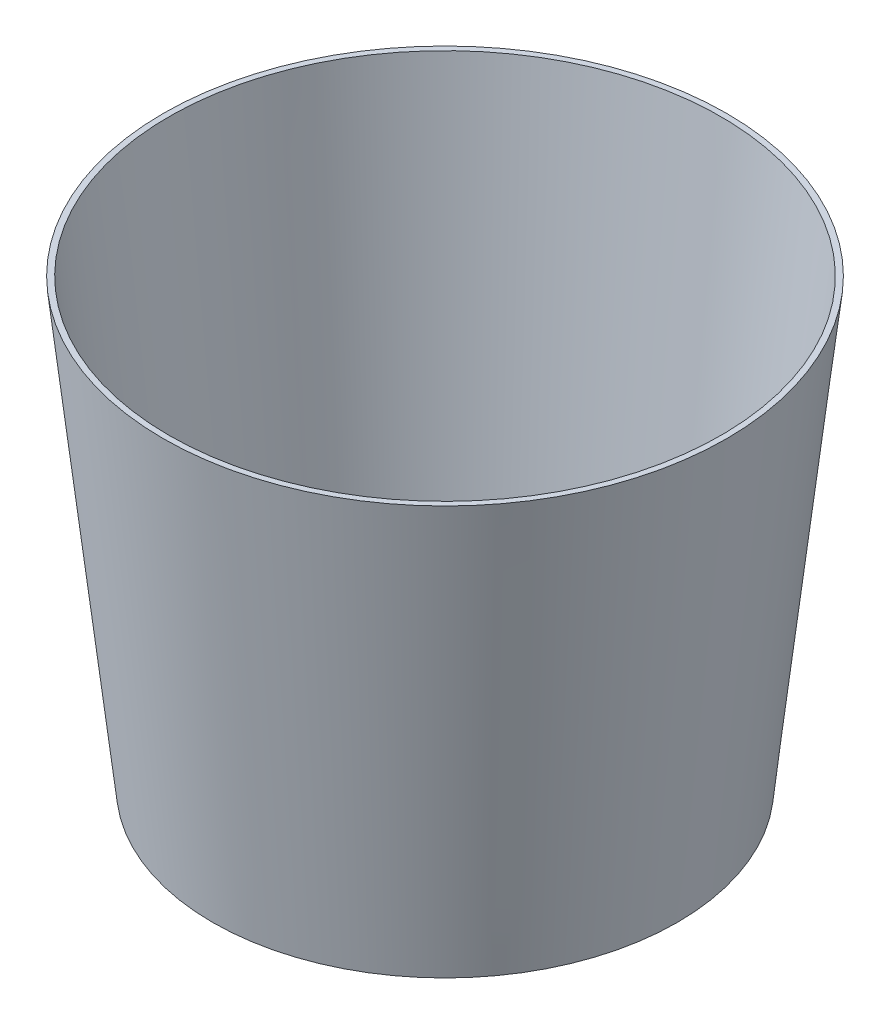
SolidWorks part; units mm, degrees
ref_plane "前视基准面" through (0, 0, 0) normal (0, 0, 1) x (1, 0, 0)
ref_plane "上视基准面" through (0, 0, 0) normal (0, 1, 0) x (1, 0, 0)
ref_plane "右视基准面" through (0, 0, 0) normal (1, 0, 0) x (0, 0, -1)
sketch "草图10" plane through (0, 0, 0) normal (1, 0, 0) x (0, 0, -1)
  line L0 (-23.5772, -17.4121) -> (-23, -17.4121)
  line L1 (-23.5772, -17.4121) -> (-28.5772, 27.5879)
  line L2 (-23, -17.4121) -> (-28, 27.5879)
  line L3 (-28.5772, 27.5879) -> (-28, 27.5879)
  line L4 (0, 30.4056) -> (0, -20.4089) construction
  dimension "D1" = 45
  dimension "D2" = 5
  dimension "D3" = 23
revolve "旋转1" add sketch "草图10" angle 360 about L4
